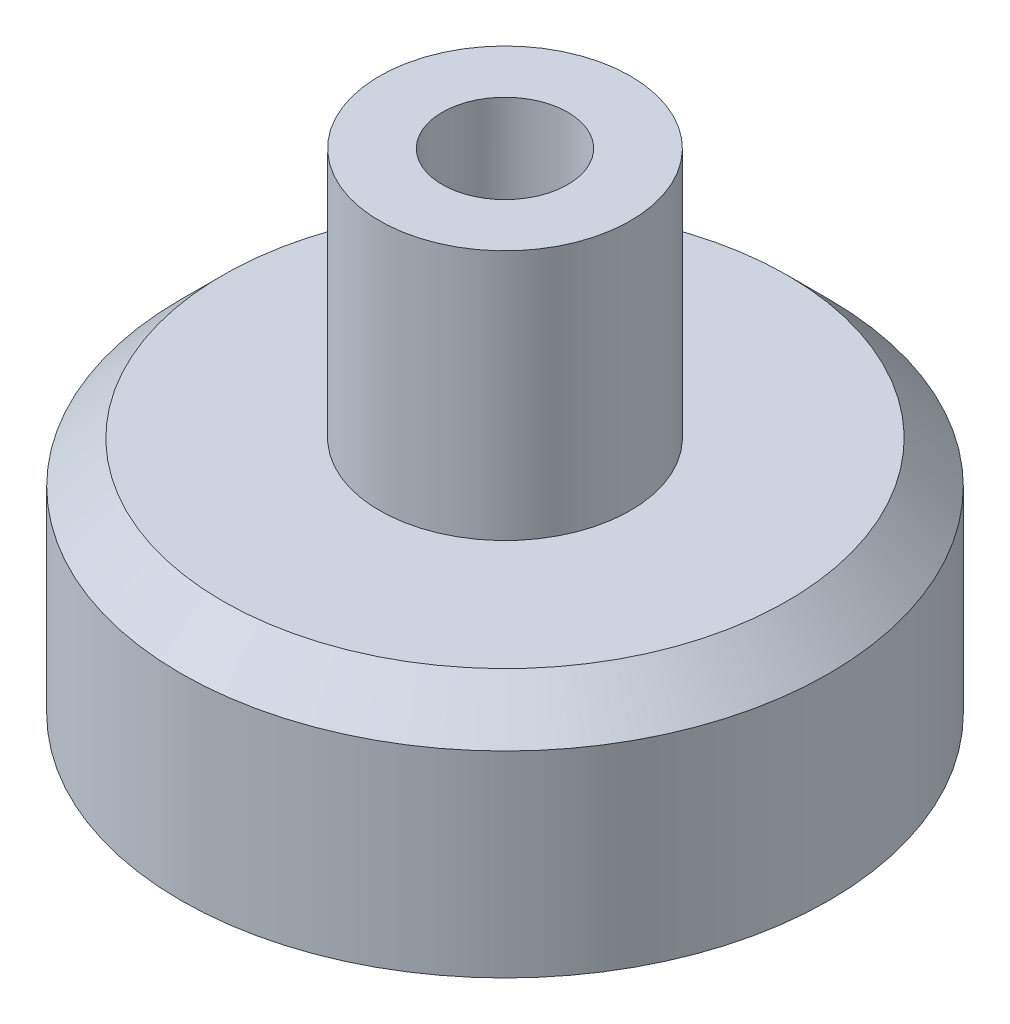
SolidWorks part; units mm, degrees
ref_plane "Front Plane" through (0, 0, 0) normal (0, 0, 1) x (1, 0, 0)
ref_plane "Top Plane" through (0, 0, 0) normal (0, 1, 0) x (1, 0, 0)
ref_plane "Right Plane" through (0, 0, 0) normal (1, 0, 0) x (0, 0, -1)
sketch "Sketch1" plane through (0, 0, 0) normal (0, 0, 1) x (1, 0, 0)
  line L0 (0, 0) -> (0, 42.1403) construction
  line L1 (-30.2866, 0) -> (33.2358, 0) construction
  line L2 (-15.5, 0) -> (-15.5, 11.4)
  line L3 (-15.5, 11.4) -> (-6, 11.4)
  line L4 (-6, 11.4) -> (-6, 23.4)
  line L5 (-6, 23.4) -> (-3, 23.4)
  line L6 (-3, 23.4) -> (-3, 9.4)
  line L7 (-3, 9.4) -> (-13.5, 9.4)
  line L8 (-13.5, 9.4) -> (-13.5, 0)
  line L9 (-13.5, 0) -> (-15.5, 0)
  dimension "D1" = 11.4
  dimension "D2" = 12
  dimension "D3" = 31
  dimension "D4" = 12
  dimension "D5" = 2
  dimension "D6" = 2
  dimension "D7" = 3
revolve "Revolve1" add sketch "Sketch1" angle 360 about L0
chamfer "Chamfer1" distance 2 angle 45 2 edges at (0, 9.4, -13.5) (0, 11.4, -15.5)
chamfer "Chamfer2" distance 2 angle 45 1 edges at (0, 9.4, -3)
